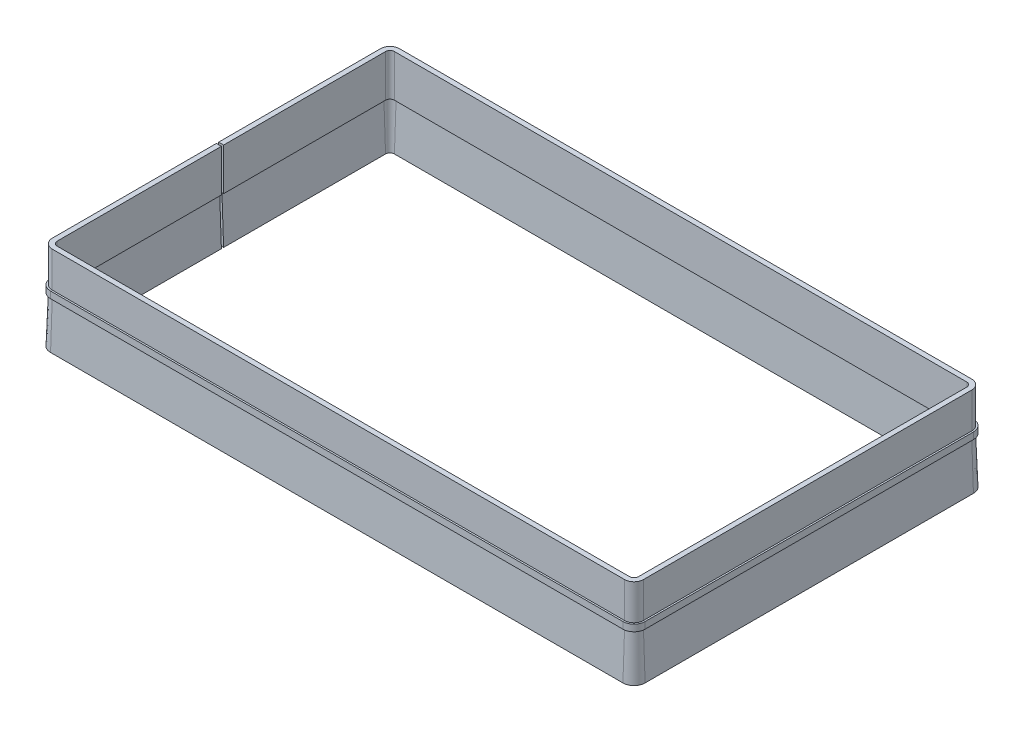
SolidWorks part; units mm, degrees
material "Aluminium"
ref_plane "Front Plane" through (0, 0, 0) normal (0, 0, 1) x (1, 0, 0)
ref_plane "Top Plane" through (0, 0, 0) normal (0, 1, 0) x (1, 0, 0)
ref_plane "Right Plane" through (0, 0, 0) normal (1, 0, 0) x (0, 0, -1)
sketch "Sketch1" plane through (0, 0, 0) normal (0, 1, 0) x (1, 0, 0)
  line L0 (0, 76) -> (0, -76) construction
  line L1 (-129, 76) -> (129, 76)
  line L2 (-131, 74) -> (-131, 1)
  line L3 (-129, -76) -> (129, -76)
  line L4 (131, 74) -> (131, -74)
  line L5 (0, 0) -> (-131, 0) construction
  line L7 (-131, 0) -> (-131, -74)
  arc A0 (129, 76) -> (131, 74) centre (129, 74) cw
  arc A1 (129, -76) -> (131, -74) centre (129, -74) ccw
  arc A2 (-131, -74) -> (-129, -76) centre (-129, -74) ccw
  arc A3 (-129, 76) -> (-131, 74) centre (-129, 74) ccw
  point P12 (131, 76)
  point P15 (131, -76)
  point P20 (-131, 76)
  dimension "D4" = 2
  dimension "D1" = 262
  dimension "D2" = 152
  dimension "D3" = 1
sketch "Sketch2" plane through (0, 0, 0) normal (0, 0, 1) x (1, 0, 0)
  line L0 (-131, 0) -> (-131, -19)
  line L1 (-131, -19) -> (-131.75, -19)
  line L2 (-134, -19) -> (-134, -16)
  line L3 (-134, -16) -> (-133.25, -16)
  line L4 (-133.25, -16) -> (-133.25, 0)
  line L5 (-133.25, 0) -> (-131, 0)
  line L6 (-133.25, -19) -> (-134, -40)
  line L7 (-134, -40) -> (-131, -40)
  line L8 (-131, -40) -> (-131.75, -19)
  line L9 (-133.25, -19) -> (-134, -19)
  dimension "D1" = 3
  dimension "D2" = 40
  dimension "D3" = 21
  dimension "D4" = 1.5
  dimension "D5" = 3
sweep "Sweep1" add profiles "Sketch2" path "Sketch1"
